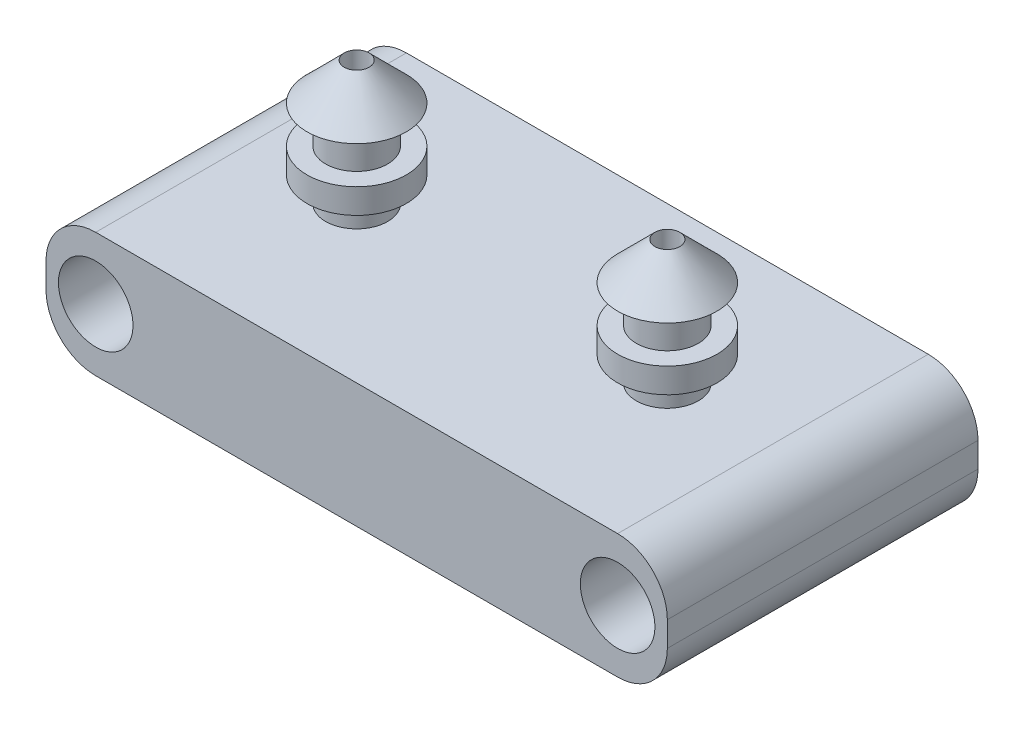
SolidWorks part; units mm, degrees
ref_plane "Front Plane" through (0, 0, 0) normal (0, 0, 1) x (1, 0, 0)
ref_plane "Top Plane" through (0, 0, 0) normal (0, 1, 0) x (1, 0, 0)
ref_plane "Right Plane" through (0, 0, 0) normal (1, 0, 0) x (0, 0, -1)
sketch "Sketch1" plane through (0, 0, 0) normal (0, 1, 0) x (1, 0, 0)
  line L0 (12.5, 0) -> (-12.5, 0) construction
  line L1 (-12.5, 6.25) -> (12.5, 6.25)
  line L2 (-12.5, 6.25) -> (-12.5, -6.25)
  line L3 (-12.5, -6.25) -> (12.5, -6.25)
  line L4 (12.5, 6.25) -> (12.5, -6.25)
  point P4 (0, 0)
  point P5 (0, 0)
  point P7 (0, 0)
  dimension "D1" = 25
  dimension "D2" = 12.5
extrude "Boss-Extrude1" add sketch "Sketch1" along normal blind 5
sketch "Sketch3" plane through (0, 0, 0) normal (0, 0, 1) x (1, 0, 0)
  line L1 (-12.5, 5) -> (0, 5) construction
  line L3 (-12.5, 5) -> (12.5, 5) construction
  line L4 (-6.75, 5) -> (-7.5, 5)
  line L5 (-7.5, 5) -> (-7.5, 6)
  line L6 (-7.5, 6) -> (-8.25, 6)
  line L7 (-8.25, 6) -> (-8.25, 7)
  line L8 (-8.25, 7) -> (-7.4958, 7)
  line L9 (-7.4958, 7) -> (-7.4958, 8.5)
  line L10 (-7.4958, 8.5) -> (-8.25, 8.5)
  line L11 (-8.25, 8.5) -> (-6.75, 10)
  line L12 (-6.75, 10) -> (-6.75, 5)
  line L13 (-6.25, 11.5534) -> (-6.25, -2.0927) construction
  point P4 (0, 0)
  point P9 (-6.25, 5)
  dimension "D1" = 5
  dimension "D2" = 1
  dimension "D3" = 1.5
  dimension "D4" = 1
  dimension "D5" = 1
  dimension "D6" = 2
  dimension "D7" = 2
  dimension "D8" = 0.7458
  dimension "D9" = 0.75
revolve "Revolve1" add sketch "Sketch3" angle 360 about L13
fillet "Fillet1" radius 2 4 edges at (-12.5, 0, 0) (-12.5, 5, 0) (12.5, 0, 0) (12.5, 5, 0)
sketch "Sketch4" plane through (0, 0, -6.25) normal (0, 0, -1) x (-1, 0, 0)
  line L0 (-10.5, 0) -> (10.5, 0) construction
  line L1 (12.5, 3) -> (12.5, 2) construction
  line L2 (-12.5, 3) -> (-12.5, 2) construction
  circle A0 centre (10.5, 2.5) radius 1.5
  circle A1 centre (-10.5, 2.5) radius 1.5
  dimension "D5" = 3
  dimension "D6" = 3
  dimension "D1" = 2
  dimension "D2" = 2
  dimension "D3" = 2.5
  dimension "D4" = 2.5
extrude "Cut-Extrude1" cut sketch "Sketch4" against normal through all
mirror "Mirror1" about plane through (0, 0, 0) normal (1, 0, 0) of "Revolve1"
sketch "Sketch5" plane through (0, 0, 0) normal (0, -1, 0) x (1, 0, 0)
  line L1 (8.5, -4.25) -> (-8.5, -4.25)
  line L2 (8.5, -4.25) -> (8.5, 4.25)
  line L3 (8.5, 4.25) -> (-8.5, 4.25)
  line L4 (-8.5, -4.25) -> (-8.5, 4.25)
  line L6 (10.5, -6.25) -> (-10.5, -6.25) construction
  line L7 (-10.5, 6.25) -> (10.5, 6.25) construction
  line L8 (10.5, -6.25) -> (10.5, 6.25) construction
  line L9 (-10.5, 6.25) -> (-10.5, -6.25) construction
  dimension "D1" = 2
  dimension "D2" = 2
  dimension "D3" = 2
  dimension "D4" = 2
extrude "Cut-Extrude2" cut sketch "Sketch5" against normal blind 2.5
sketch "Sketch6" plane through (0, 2.5, 0) normal (0, -1, 0) x (1, 0, 0)
  line L0 (0, 0) -> (2.5, 0) construction
  line L1 (0.5, 0.15) -> (0.5, 0.85)
  line L2 (2.65, 0) -> (3.35, 0)
  line L3 (2.5, 0.15) -> (2.5, 0.85)
  line L4 (2.65, 1) -> (3.35, 1)
  line L5 (3.5, 0.15) -> (3.5, 0.85)
  line L6 (0.65, 0) -> (1.35, 0)
  line L7 (1.5, 0.15) -> (1.5, 0.85)
  line L8 (0.65, 1) -> (1.35, 1)
  line L9 (-1.5, 0.15) -> (-1.5, 0.85)
  line L10 (-1.35, 0) -> (-0.65, 0)
  line L11 (-0.5, 0.15) -> (-0.5, 0.85)
  line L12 (-1.35, 1) -> (-0.65, 1)
  line L13 (-3.5, 0.15) -> (-3.5, 0.85)
  line L14 (-3.35, 0) -> (-2.65, 0)
  line L15 (-2.5, 0.15) -> (-2.5, 0.85)
  line L16 (-3.35, 1) -> (-2.65, 1)
  arc A0 (2.5, 0.85) -> (2.65, 1) centre (2.65, 0.85) cw
  arc A1 (3.35, 1) -> (3.5, 0.85) centre (3.35, 0.85) cw
  arc A2 (3.35, 0) -> (3.5, 0.15) centre (3.35, 0.15) ccw
  arc A3 (2.5, 0.15) -> (2.65, 0) centre (2.65, 0.15) ccw
  arc A4 (0.5, 0.15) -> (0.65, 0) centre (0.65, 0.15) ccw
  arc A5 (0.5, 0.85) -> (0.65, 1) centre (0.65, 0.85) cw
  arc A6 (1.35, 0) -> (1.5, 0.15) centre (1.35, 0.15) ccw
  arc A7 (1.35, 1) -> (1.5, 0.85) centre (1.35, 0.85) cw
  arc A8 (-1.5, 0.15) -> (-1.35, 0) centre (-1.35, 0.15) ccw
  arc A9 (-1.5, 0.85) -> (-1.35, 1) centre (-1.35, 0.85) cw
  arc A10 (-0.65, 0) -> (-0.5, 0.15) centre (-0.65, 0.15) ccw
  arc A11 (-0.65, 1) -> (-0.5, 0.85) centre (-0.65, 0.85) cw
  arc A12 (-3.5, 0.15) -> (-3.35, 0) centre (-3.35, 0.15) ccw
  arc A13 (-3.5, 0.85) -> (-3.35, 1) centre (-3.35, 0.85) cw
  arc A14 (-2.65, 0) -> (-2.5, 0.15) centre (-2.65, 0.15) ccw
  arc A15 (-2.65, 1) -> (-2.5, 0.85) centre (-2.65, 0.85) cw
  point P10 (3.5, 1)
  point P13 (3.5, 0)
  dimension "D4" = 0.15
  dimension "D5" = 0.15
  dimension "D6" = 0.15
  dimension "D7" = 0.15
  dimension "D1" = 2.5
  dimension "D2" = 1
  dimension "D3" = 1
  dimension "D8" = 4
extrude "Boss-Extrude2" add sketch "Sketch6" along normal blind 5
